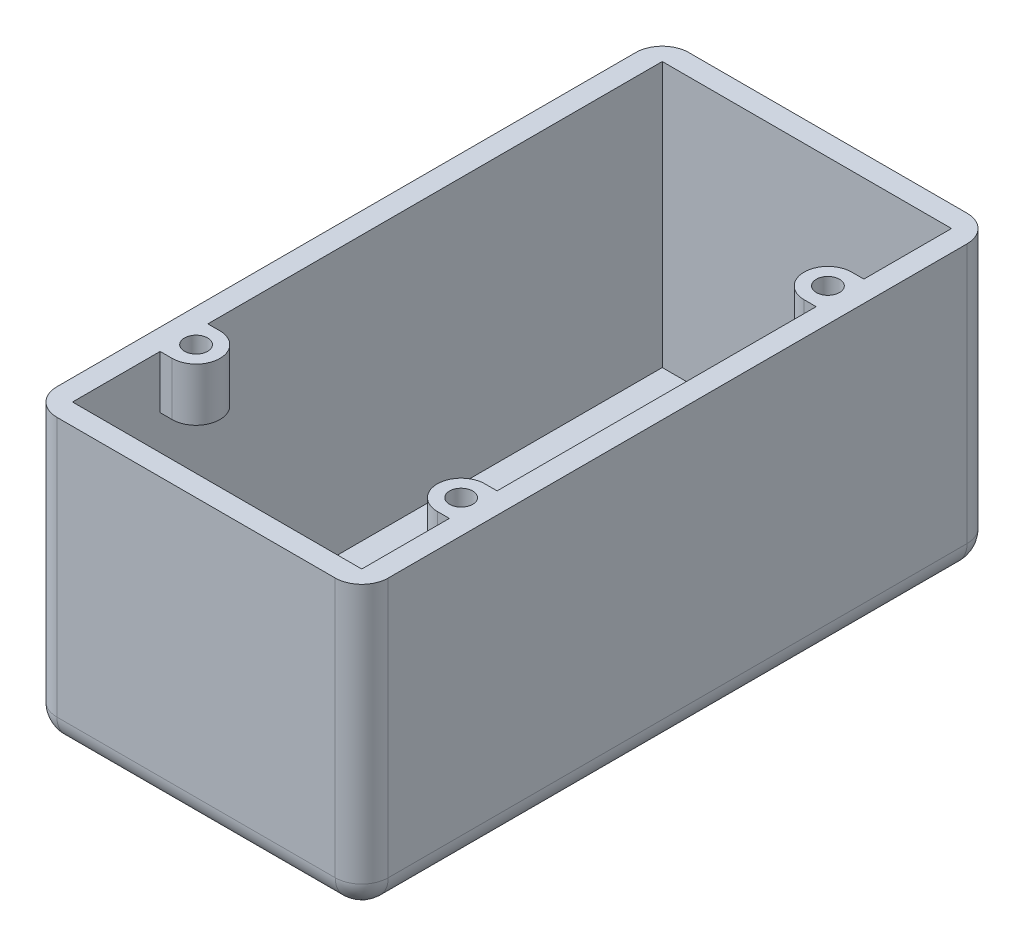
SolidWorks part; units mm, degrees
ref_plane "Front Plane" through (0, 0, 0) normal (0, 0, 1) x (1, 0, 0)
ref_plane "Top Plane" through (0, 0, 0) normal (0, 1, 0) x (1, 0, 0)
ref_plane "Right Plane" through (0, 0, 0) normal (1, 0, 0) x (0, 0, -1)
sketch "Sketch1" plane through (0, 0, 0) normal (0, 1, 0) x (1, 0, 0)
  line L1 (-25, 47.675) -> (25, 47.675)
  line L2 (-25, 47.675) -> (-25, -47.675)
  line L3 (-25, -47.675) -> (25, -47.675)
  line L4 (25, 47.675) -> (25, -47.675)
  line L5 (-25, 47.675) -> (25, -47.675) construction
  line L6 (-25, -47.675) -> (25, 47.675) construction
  line L7 (-21.825, 44.5) -> (21.825, 44.5)
  line L8 (-21.825, 44.5) -> (-21.825, -44.5)
  line L9 (-21.825, -44.5) -> (21.825, -44.5)
  line L10 (21.825, 44.5) -> (21.825, -44.5)
  line L11 (-21.825, 44.5) -> (21.825, -44.5) construction
  line L12 (-21.825, -44.5) -> (21.825, 44.5) construction
  point P0 (0, 0)
  point P6 (0, 0)
  dimension "D1" = 3.175
  dimension "D2" = 3.175
  dimension "D3" = 95.35
  dimension "D4" = 50
extrude "Boss-Extrude1" add sketch "Sketch1" along normal blind 40
sketch "Sketch2" plane through (0, 0, 0) normal (0, -1, 0) x (1, 0, 0)
  line L1 (25, -47.675) -> (-25, -47.675)
  line L2 (25, -47.675) -> (25, 47.675)
  line L3 (25, 47.675) -> (-25, 47.675)
  line L4 (-25, -47.675) -> (-25, 47.675)
extrude "Boss-Extrude2" add sketch "Sketch2" along normal blind 3.175
fillet "Fillet1" radius 4 8 edges at (25, 18.4125, 47.675) (25, 18.4125, -47.675) (-25, 18.4125, -47.675) (-25, 18.4125, 47.675) (0, -3.175, 47.675) (-25, -3.175, 0) (0, -3.175, -47.675) (25, -3.175, 0)
sketch "Sketch3" plane through (0, 0, 0) normal (0, 1, 0) x (1, 0, 0)
  line L0 (-21.825, -44.5) -> (21.825, -44.5) construction
  line L1 (-15, 33.55) -> (8.05, 33.55) construction
  line L2 (-15, 33.55) -> (-15, -24.5) construction
  line L3 (-15, -24.5) -> (8.05, -24.5) construction
  line L4 (8.05, 33.55) -> (8.05, -24.5) construction
  line L6 (-21, -43.675) -> (-21, 43.675) construction
  circle A0 centre (-15, 33.55) radius 1.3
  circle A1 centre (8.05, 33.55) radius 1.3
  circle A2 centre (8.05, -24.5) radius 1.3
  circle A3 centre (-15, -24.5) radius 1.3
  dimension "D2" = 2.6
  dimension "D1" = 58.05
  dimension "D3" = 23.05
  dimension "D4" = 20
  dimension "D5" = 6
extrude "Cut-Extrude1" cut sketch "Sketch3" against normal up to surface (3.175 mm away) up to face at (0, -3.175, 0)
sketch "Sketch4" plane through (0, 40, 0) normal (0, 1, 0) x (1, 0, 0)
  line L0 (-20, -24.075) -> (-21.825, -24.075)
  line L1 (-21.825, 44.5) -> (-21.825, -44.5) construction
  line L2 (-21.825, -24.075) -> (-21.825, -31.275)
  line L3 (-21.825, -31.275) -> (-20, -31.275)
  line L4 (0, -47.675) -> (0, 47.675) construction
  line L5 (-21, -47.675) -> (21, -47.675) construction
  line L6 (21, 47.675) -> (-21, 47.675) construction
  line L7 (-25, 43.675) -> (-25, -43.675) construction
  line L8 (21.825, -31.275) -> (20, -31.275)
  line L9 (21.825, -24.075) -> (21.825, -31.275)
  line L10 (20, -24.075) -> (21.825, -24.075)
  line L11 (-25, 0) -> (25, 0) construction
  line L12 (25, -43.675) -> (25, 43.675) construction
  line L13 (20, 24.075) -> (21.825, 24.075)
  line L14 (21.825, 24.075) -> (21.825, 31.275)
  line L15 (21.825, 31.275) -> (20, 31.275)
  arc A0 (-20, -31.275) -> (-20, -24.075) centre (-20, -27.675) ccw
  arc A1 (20, -31.275) -> (20, -24.075) centre (20, -27.675) cw
  arc A2 (20, 31.275) -> (20, 24.075) centre (20, 27.675) ccw
  dimension "D1" = 7.2
  dimension "D2" = 5
  dimension "D3" = 20
extrude "Boss-Extrude3" add sketch "Sketch4" against normal blind 8
sketch "Sketch5" plane through (0, 40, 0) normal (0, 1, 0) x (1, 0, 0)
  line L0 (0, 47.675) -> (0, -47.675) construction
  line L1 (21, 47.675) -> (-21, 47.675) construction
  line L2 (-21, -47.675) -> (21, -47.675) construction
  line L3 (-25, 0) -> (25, 0) construction
  line L4 (-25, 43.675) -> (-25, -43.675) construction
  line L5 (25, -43.675) -> (25, 43.675) construction
  circle A0 centre (-20, -27.675) radius 1.75
  circle A1 centre (20, -27.675) radius 1.75
  circle A2 centre (20, 27.675) radius 1.75
  dimension "D1" = 3.5
extrude "Cut-Extrude2" cut sketch "Sketch5" against normal blind 5
